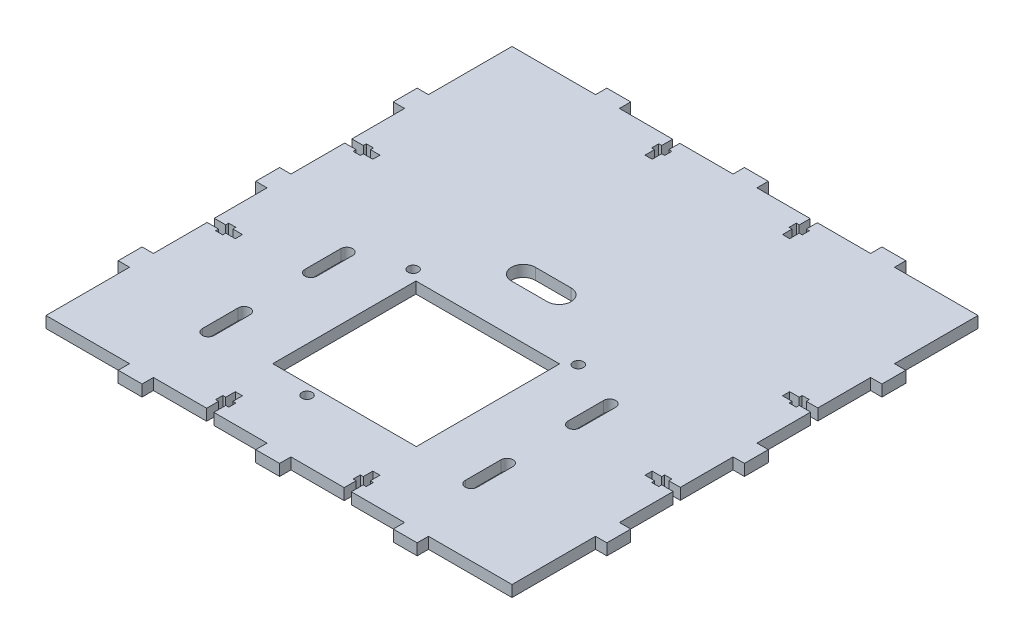
SolidWorks part; units mm, degrees
material "Pine"
ref_plane "Front Plane" through (0, 0, 0) normal (0, 0, 1) x (1, 0, 0)
ref_plane "Top Plane" through (0, 0, 0) normal (0, 1, 0) x (1, 0, 0)
ref_plane "Right Plane" through (0, 0, 0) normal (1, 0, 0) x (0, 0, -1)
sketch "Sketch1" plane through (0, 0, 0) normal (0, 1, 0) x (1, 0, 0)
  line L1 (0, 0) -> (-195.25, 0)
  line L2 (0, 0) -> (0, 195.25)
  line L3 (0, 195.25) -> (-195.25, 195.25)
  line L4 (-195.25, 0) -> (-195.25, 195.25)
  dimension "D1" = 195.25
extrude "Boss-Extrude1" add sketch "Sketch1" along normal blind 4.75
sketch "Sketch2" plane through (0, 4.75, 0) normal (0, 1, 0) x (1, 0, 0)
  line L0 (0, 195.25) -> (-195.25, 195.25) construction
  line L1 (-160.25, 195.25) -> (-150.25, 195.25)
  line L2 (-160.25, 195.25) -> (-160.25, 200)
  line L3 (-160.25, 200) -> (-150.25, 200)
  line L4 (-150.25, 195.25) -> (-150.25, 200)
  line L5 (-150.25, 197.625) -> (-102.625, 197.625) construction
  line L6 (-102.625, 200) -> (-92.625, 200)
  line L7 (-102.625, 200) -> (-102.625, 195.25)
  line L8 (-102.625, 195.25) -> (-92.625, 195.25)
  line L9 (-92.625, 200) -> (-92.625, 195.25)
  line L10 (-45, 200) -> (-35, 200)
  line L11 (-45, 200) -> (-45, 195.25)
  line L12 (-45, 195.25) -> (-35, 195.25)
  line L13 (-35, 200) -> (-35, 195.25)
  line L14 (-92.625, 197.625) -> (-45, 197.625) construction
  line L15 (0, 0) -> (0, 195.25) construction
  line L16 (-195.25, 0) -> (0, 0) construction
  line L17 (-195.25, 195.25) -> (-195.25, 0) construction
  line L18 (0, 160.25) -> (4.75, 160.25)
  line L19 (0, 160.25) -> (0, 150.25)
  line L20 (0, 150.25) -> (4.75, 150.25)
  line L21 (4.75, 160.25) -> (4.75, 150.25)
  line L22 (4.75, 102.625) -> (0, 102.625)
  line L23 (4.75, 102.625) -> (4.75, 92.625)
  line L24 (4.75, 92.625) -> (0, 92.625)
  line L25 (0, 102.625) -> (0, 92.625)
  line L26 (4.75, 45) -> (0, 45)
  line L27 (4.75, 45) -> (4.75, 35)
  line L28 (4.75, 35) -> (0, 35)
  line L29 (0, 45) -> (0, 35)
  line L30 (-35, 0) -> (-35, -4.75)
  line L31 (-35, 0) -> (-45, 0)
  line L32 (-45, 0) -> (-45, -4.75)
  line L33 (-35, -4.75) -> (-45, -4.75)
  line L34 (-92.625, -4.75) -> (-92.625, 0)
  line L35 (-92.625, -4.75) -> (-102.625, -4.75)
  line L36 (-102.625, -4.75) -> (-102.625, 0)
  line L37 (-92.625, 0) -> (-102.625, 0)
  line L38 (-150.25, -4.75) -> (-150.25, 0)
  line L39 (-150.25, -4.75) -> (-160.25, -4.75)
  line L40 (-160.25, -4.75) -> (-160.25, 0)
  line L41 (-150.25, 0) -> (-160.25, 0)
  line L42 (-195.25, 35) -> (-200, 35)
  line L43 (-195.25, 35) -> (-195.25, 45)
  line L44 (-195.25, 45) -> (-200, 45)
  line L45 (-200, 35) -> (-200, 45)
  line L46 (-200, 92.625) -> (-195.25, 92.625)
  line L47 (-200, 92.625) -> (-200, 102.625)
  line L48 (-200, 102.625) -> (-195.25, 102.625)
  line L49 (-195.25, 92.625) -> (-195.25, 102.625)
  line L50 (-200, 150.25) -> (-195.25, 150.25)
  line L51 (-200, 150.25) -> (-200, 160.25)
  line L52 (-200, 160.25) -> (-195.25, 160.25)
  line L53 (-195.25, 150.25) -> (-195.25, 160.25)
  circle A0 centre (-97.625, 97.625) radius 97.625 construction
  dimension "D1" = 4.75
  dimension "D2" = 10
  dimension "D3" = 35
  dimension "D4" = 35
  dimension "D5" = 4
extrude "Boss-Extrude2" add sketch "Sketch2" against normal blind 4.75
sketch "Sketch3" plane through (0, 4.75, 0) normal (0, 1, 0) x (1, 0, 0)
  line L0 (-150.25, 0) -> (-102.625, 0) construction
  line L1 (-127.9375, 0) -> (-124.9375, 0)
  line L2 (-127.9375, 0) -> (-127.9375, 12)
  line L3 (-127.9375, 12) -> (-124.9375, 12)
  line L4 (-124.9375, 0) -> (-124.9375, 12)
  line L5 (-92.625, 0) -> (-45, 0) construction
  line L6 (-129.1875, 8) -> (-123.6875, 8)
  line L7 (-129.1875, 8) -> (-129.1875, 5)
  line L8 (-129.1875, 5) -> (-123.6875, 5)
  line L9 (-123.6875, 8) -> (-123.6875, 5)
  line L10 (-70.3125, 0) -> (-67.3125, 0)
  line L11 (-70.3125, 0) -> (-70.3125, 12)
  line L12 (-70.3125, 12) -> (-67.3125, 12)
  line L13 (-67.3125, 0) -> (-67.3125, 12)
  line L15 (-71.5625, 8) -> (-66.0625, 8)
  line L16 (-71.5625, 8) -> (-71.5625, 5)
  line L17 (-71.5625, 5) -> (-66.0625, 5)
  line L18 (-66.0625, 8) -> (-66.0625, 5)
  point P20 (-126.4375, 8)
  point P21 (-126.4375, 12)
  point P22 (-68.8125, 8)
  point P23 (-68.8125, 12)
  point P24 (-126.4375, 0)
  point P25 (-68.8125, 0)
  dimension "D1" = 12
  dimension "D2" = 5
  dimension "D3" = 3
  dimension "D4" = 5.5
  dimension "D5" = 3
extrude "Cut-Extrude1" cut sketch "Sketch3" against normal blind 4.75 contours L2 L3 L4 L1 | L6 L9 L8 L7 | L12 L13 L10 L11 | L15 L18 L17 L16
pattern_circular "CirPattern1" count 4 over 360 about axis through (-97.625, 0, -97.8313) along (0, 1, 0) of "Cut-Extrude1"
sketch "Sketch4" plane through (0, 4.75, 0) normal (0, 1, 0) x (1, 0, 0)
  line L0 (-155.25, 86.01) -> (-155.25, 71.01) construction
  line L1 (-130.25, 90.01) -> (-70.08, 90.01)
  line L2 (-130.25, 90.01) -> (-130.25, 30)
  line L3 (-130.25, 30) -> (-70.08, 30)
  line L4 (-55.08, 20) -> (-55.08, 100.01)
  line L5 (-55.08, 100.01) -> (-145.25, 100.01)
  line L6 (-145.25, 100.01) -> (-145.25, 20)
  line L7 (-145.25, 20) -> (-55.08, 20)
  line L8 (-55.08, 20) -> (-55.08, 100.01) construction
  line L9 (-55.08, 100.01) -> (-145.25, 100.01) construction
  line L10 (-145.25, 100.01) -> (-145.25, 20) construction
  line L11 (-145.25, 20) -> (-55.08, 20) construction
  line L12 (-70.08, 90.01) -> (-70.08, 30)
  line L15 (-155.25, 43) -> (-155.25, 28) construction
  line L16 (-152.75, 43) -> (-152.75, 28)
  line L17 (-157.75, 43) -> (-157.75, 28)
  line L18 (-45.08, 43) -> (-45.08, 28) construction
  line L19 (-42.58, 43) -> (-42.58, 28)
  line L20 (-47.58, 43) -> (-47.58, 28)
  line L21 (-45.08, 86.01) -> (-45.08, 71.01) construction
  line L22 (-42.58, 86.01) -> (-42.58, 71.01)
  line L23 (-47.58, 86.01) -> (-47.58, 71.01)
  line L24 (-110.25, 115.01) -> (-95.25, 115.01) construction
  line L25 (-110.25, 120.01) -> (-95.25, 120.01)
  line L26 (-110.25, 110.01) -> (-95.25, 110.01)
  line L27 (-152.75, 86.01) -> (-152.75, 71.01)
  line L28 (-157.75, 86.01) -> (-157.75, 71.01)
  circle A0 centre (-111.595, 25.715) radius 2.15 construction
  circle A1 centre (-65.875, 93.66) radius 2.15 construction
  circle A2 centre (-135.09, 93.66) radius 2.15 construction
  circle A3 centre (-111.595, 25.715) radius 2.15
  circle A4 centre (-65.875, 93.66) radius 2.15
  circle A5 centre (-135.09, 93.66) radius 2.15
  arc A8 (-152.75, 43) -> (-157.75, 43) centre (-155.25, 43) ccw
  arc A9 (-157.75, 28) -> (-152.75, 28) centre (-155.25, 28) ccw
  arc A10 (-42.58, 43) -> (-47.58, 43) centre (-45.08, 43) ccw
  arc A11 (-47.58, 28) -> (-42.58, 28) centre (-45.08, 28) ccw
  arc A12 (-42.58, 86.01) -> (-47.58, 86.01) centre (-45.08, 86.01) ccw
  arc A13 (-47.58, 71.01) -> (-42.58, 71.01) centre (-45.08, 71.01) ccw
  arc A14 (-110.25, 120.01) -> (-110.25, 110.01) centre (-110.25, 115.01) ccw
  arc A15 (-95.25, 110.01) -> (-95.25, 120.01) centre (-95.25, 115.01) ccw
  arc A16 (-152.75, 86.01) -> (-157.75, 86.01) centre (-155.25, 86.01) ccw
  arc A17 (-157.75, 71.01) -> (-152.75, 71.01) centre (-155.25, 71.01) ccw
  point P17 (-130.25, 60.005)
  point P18 (-145.25, 60.005)
  point P19 (-100.165, 30)
  point P20 (-100.165, 20)
  point P23 (-155.25, 78.51)
  point P28 (-155.25, 35.5)
  point P35 (-45.08, 35.5)
  point P42 (-45.08, 78.51)
  point P49 (-102.75, 115.01)
  point P56 (0, 0)
  point P57 (0, 0)
  point P58 (0, 0)
  point P59 (0, 0)
  dimension "D2" = 15
  dimension "D3" = 10
  dimension "D4" = 5
  dimension "D5" = 15
  dimension "D6" = 8
  dimension "D7" = 14
  dimension "D8" = 10
  dimension "D9" = 10
  dimension "D10" = 10
  dimension "D11" = 10
  dimension "D12" = 35
  dimension "D13" = 10
  dimension "D14" = 15
  dimension "D1" = 0
extrude "Cut-Extrude2" cut sketch "Sketch4" against normal through all
